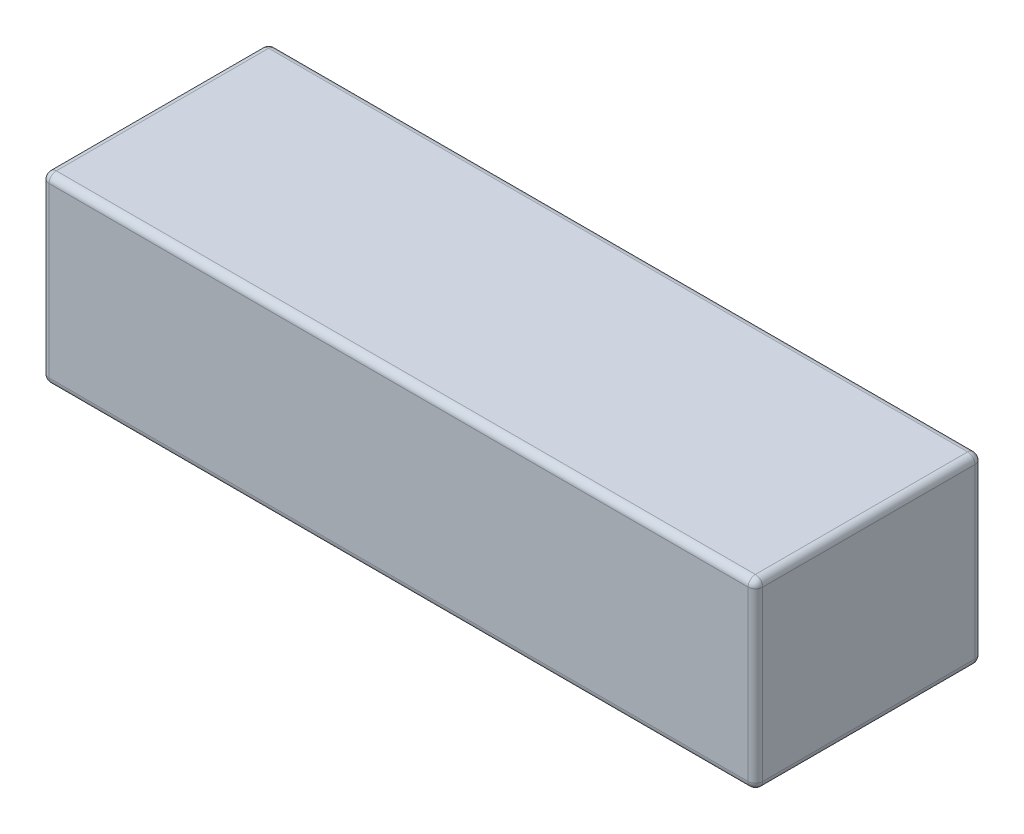
SolidWorks part; units mm, degrees
ref_plane "Front Plane" through (0, 0, 0) normal (0, 0, 1) x (1, 0, 0)
ref_plane "Top Plane" through (0, 0, 0) normal (0, 1, 0) x (1, 0, 0)
ref_plane "Right Plane" through (0, 0, 0) normal (1, 0, 0) x (0, 0, -1)
sketch "Sketch1" plane through (0, 0, 0) normal (0, 1, 0) x (1, 0, 0)
  line L1 (123.825, 39.37) -> (-123.825, 39.37)
  line L2 (123.825, 39.37) -> (123.825, -39.37)
  line L3 (123.825, -39.37) -> (-123.825, -39.37)
  line L4 (-123.825, 39.37) -> (-123.825, -39.37)
  line L5 (123.825, 39.37) -> (-123.825, -39.37) construction
  line L6 (123.825, -39.37) -> (-123.825, 39.37) construction
  point P0 (0, 0)
  dimension "D1" = 247.65
  dimension "D2" = 78.74
extrude "Boss-Extrude1" add sketch "Sketch1" along normal blind 63.5
fillet "Fillet1" radius 2.54 12 edges at (0, 0, -39.37) (123.825, 31.75, -39.37) (123.825, 0, 0) (0, 63.5, -39.37) (123.825, 63.5, 0) (-123.825, 31.75, -39.37) (-123.825, 63.5, 0) (-123.825, 0, 0) (-123.825, 31.75, 39.37) (0, 63.5, 39.37) (123.825, 31.75, 39.37) (0, 0, 39.37)
